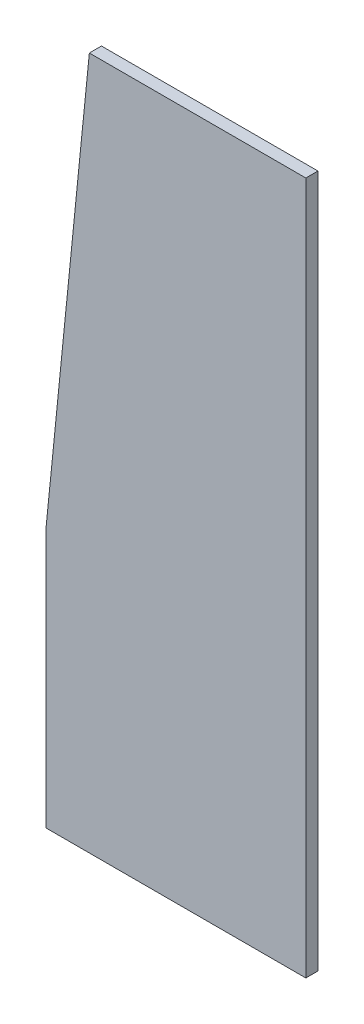
SolidWorks part; units mm, degrees
ref_plane "Front Plane" through (0, 0, 0) normal (0, 0, 1) x (1, 0, 0)
ref_plane "Top Plane" through (0, 0, 0) normal (0, 1, 0) x (1, 0, 0)
ref_plane "Right Plane" through (0, 0, 0) normal (1, 0, 0) x (0, 0, -1)
sketch "Sketch1" plane through (0, 0, 0) normal (0, 0, 1) x (1, 0, 0)
  line L1 (-42.9529, 356.7886) -> (-42.9529, 280.5886)
  line L2 (-42.9529, 280.5886) -> (33.2471, 280.5886)
  line L4 (33.2471, 483.7886) -> (-30.2529, 483.7886)
  line L5 (33.2471, 280.5886) -> (33.2471, 483.7886)
  line L6 (-42.9529, 356.7886) -> (-30.2529, 483.7886)
  circle A0 centre (-7.3929, 312.3386) radius 17.4625
  circle A1 centre (-17.5529, 375.8386) radius 3.175
  circle A2 centre (-17.5529, 420.2886) radius 3.175
  circle A3 centre (-17.5529, 464.7386) radius 3.175
  circle A4 centre (20.5471, 464.7386) radius 3.175
  circle A5 centre (20.5471, 420.2886) radius 3.175
  circle A6 centre (20.5471, 375.8386) radius 3.175
extrude "Boss-Extrude1" add sketch "Sketch1" along normal blind 3.556 contours L6 L4 L5 L2 L1
